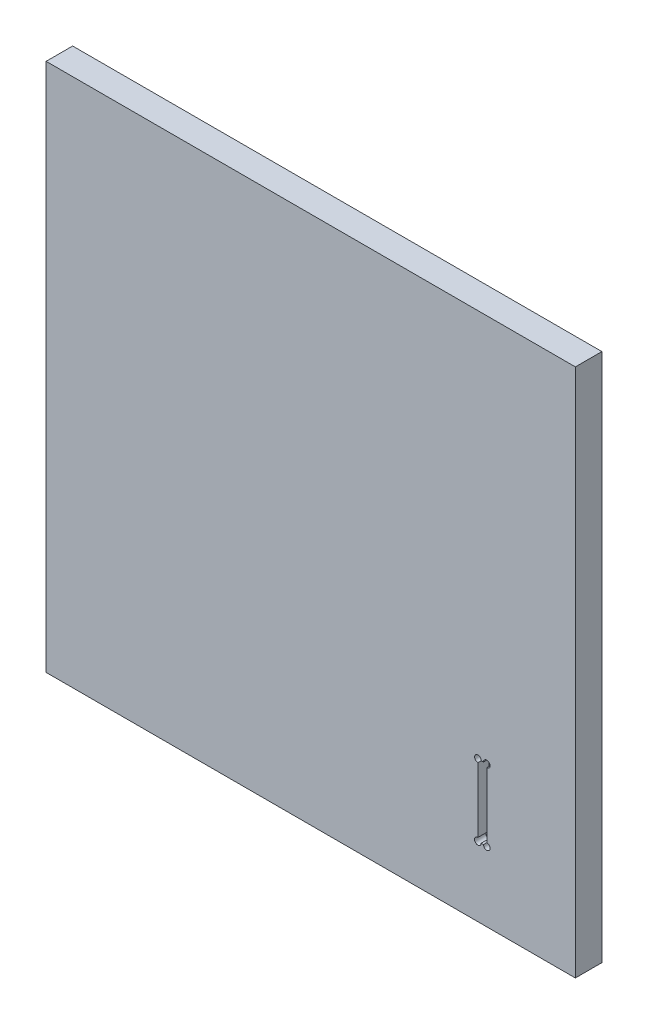
SolidWorks part; units mm, degrees
ref_plane "Front" through (0, 0, 0) normal (0, 0, 1) x (1, 0, 0)
ref_plane "Top" through (0, 0, 0) normal (0, 1, 0) x (1, 0, 0)
ref_plane "Right" through (0, 0, 0) normal (1, 0, 0) x (0, 0, -1)
sketch "Sketch1" plane through (0, 0, 0) normal (0, 0, 1) x (1, 0, 0)
  line L1 (-190, 190) -> (190, 190)
  line L2 (-190, 190) -> (-190, -190)
  line L3 (-190, -190) -> (190, -190)
  line L4 (190, 190) -> (190, -190)
  line L5 (-190, 190) -> (190, -190) construction
  line L6 (-190, -190) -> (190, 190) construction
  point P0 (0, 0)
  dimension "D1" = 380
extrude "Spoilboard" add sketch "Sketch1" along normal blind 19.05
sketch "Sketch2" plane through (0, 0, 19.05) normal (0, 0, 1) x (1, 0, 0)
  line L6 (120, -137.6187) -> (120, -91.0811)
  line L8 (126.4, -137.6187) -> (126.4, -91.0812)
  line L9 (-190, 190) -> (-190, -190) construction
  line L13 (122.3812, -140) -> (124.0187, -140)
  line L14 (122.4063, -88.7) -> (124.0187, -88.7)
  arc A2 (126.4, -91.0812) -> (124.0187, -88.7) centre (126.4, -88.7) ccw
  arc A3 (122.4063, -88.7) -> (120, -91.0811) centre (120.025, -88.7) ccw
  arc A4 (120, -137.6187) -> (122.3812, -140) centre (120, -140) ccw
  arc A5 (124.0187, -140) -> (126.4, -137.6187) centre (126.4, -140) ccw
  dimension "D5" = 4.7625
  dimension "D2" = 310
extrude "Slot" cut sketch "Sketch2" against normal blind 8
